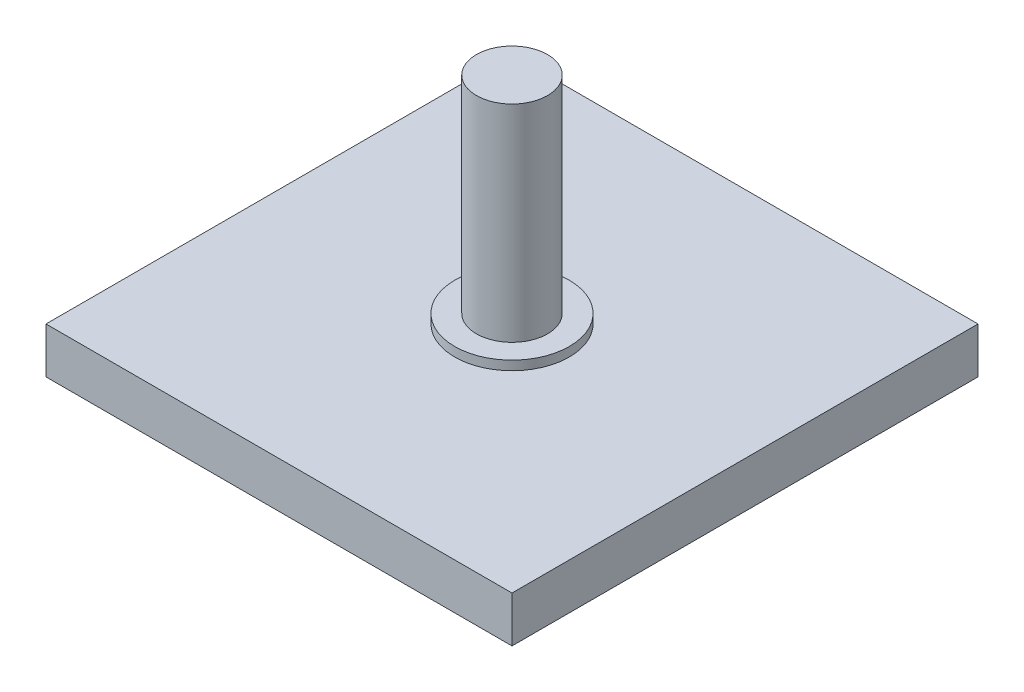
SolidWorks part; units mm, degrees
ref_plane "Front Plane" through (0, 0, 0) normal (0, 0, 1) x (1, 0, 0)
ref_plane "Top Plane" through (0, 0, 0) normal (0, 1, 0) x (1, 0, 0)
ref_plane "Right Plane" through (0, 0, 0) normal (1, 0, 0) x (0, 0, -1)
sketch "Sketch1" plane through (0, 0, 0) normal (0, 1, 0) x (1, 0, 0)
  line L1 (-50.8, -50.8) -> (50.8, -50.8)
  line L2 (-50.8, -50.8) -> (-50.8, 50.8)
  line L3 (-50.8, 50.8) -> (50.8, 50.8)
  line L4 (50.8, -50.8) -> (50.8, 50.8)
  line L5 (-50.8, -50.8) -> (50.8, 50.8) construction
  line L6 (-50.8, 50.8) -> (50.8, -50.8) construction
  point P0 (0, 0)
  dimension "D1" = 101.6
extrude "Boss-Extrude1" add sketch "Sketch1" along normal blind 10
sketch "Sketch2" plane through (0, 0, 0) normal (0, -1, 0) x (-1, 0, 0)
  circle A0 centre (0, 0) radius 5
  dimension "D1" = 10
extrude "Cut-Extrude1" cut sketch "Sketch2" against normal blind 5
sketch "Sketch3" plane through (0, 10, 0) normal (0, 1, 0) x (1, 0, 0)
  circle A0 centre (0, 0) radius 12.5
  dimension "D1" = 25
extrude "Boss-Extrude2" add sketch "Sketch3" along normal blind 2
sketch "Sketch4" plane through (0, 12, 0) normal (0, 1, 0) x (1, 0, 0)
  circle A0 centre (0, 0) radius 7.75
  dimension "D1" = 15.5
extrude "Boss-Extrude3" add sketch "Sketch4" along normal blind 45
